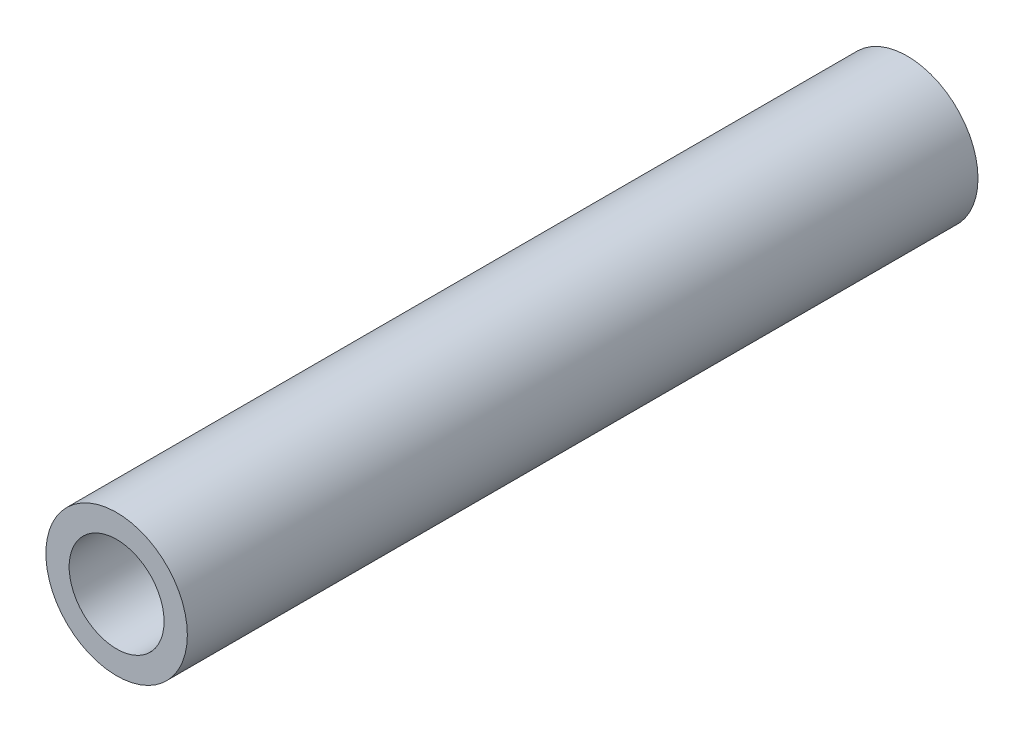
SolidWorks part; units mm, degrees
ref_plane "Front Plane" through (0, 0, 0) normal (0, 0, 1) x (1, 0, 0)
ref_plane "Top Plane" through (0, 0, 0) normal (0, 1, 0) x (1, 0, 0)
ref_plane "Right Plane" through (0, 0, 0) normal (1, 0, 0) x (0, 0, -1)
sketch "Sketch1" plane through (0, 0, 0) normal (0, 0, 1) x (1, 0, 0)
  circle A0 centre (0, 0) radius 1.99
  circle A1 centre (0, 0) radius 1.335
  dimension "D1" = 3.98
  dimension "D2" = 2.67
extrude "Boss-Extrude1" add sketch "Sketch1" along normal blind 22.24
